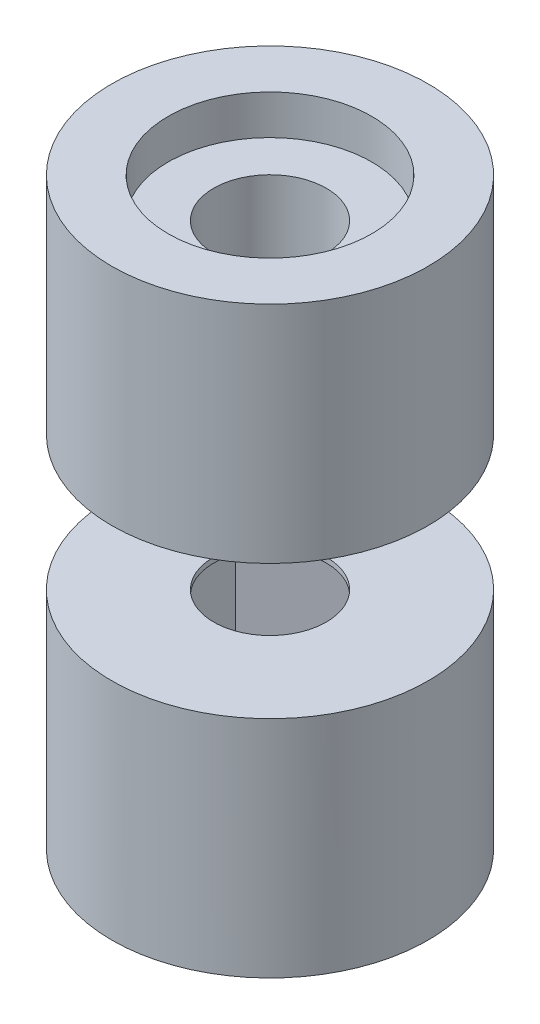
SolidWorks part; units mm, degrees
ref_plane "Front Plane" through (0, 0, 0) normal (0, 0, 1) x (1, 0, 0)
ref_plane "Top Plane" through (0, 0, 0) normal (0, 1, 0) x (1, 0, 0)
ref_plane "Right Plane" through (0, 0, 0) normal (1, 0, 0) x (0, 0, -1)
sketch "Sketch1" plane through (0, 0, 0) normal (0, 1, 0) x (1, 0, 0)
  circle A0 centre (0, 0) radius 8
extrude "Boss-Extrude1" add sketch "Sketch1" along normal blind 29.524
sketch "Sketch2" plane through (0, 0, 0) normal (0, 0, 1) x (1, 0, 0)
  line L0 (-10.2, 11.362) -> (10.2, 11.362)
  line L1 (10.2, 11.362) -> (10.2, 18.162)
  line L2 (10.2, 18.162) -> (-10.2, 18.162)
  line L3 (-10.2, 18.162) -> (-10.2, 11.362)
extrude "Cut-Extrude1" cut sketch "Sketch2" against normal through all and the other way through all
sketch "Sketch3" plane through (0, 0, 0) normal (0, 1, 0) x (1, 0, 0)
  circle A0 centre (0, 0) radius 2.85
extrude "Cut-Extrude2" cut sketch "Sketch3" along normal blind 29.524
ref_plane "Plane1" through (0, 29.524, 0) normal (0, 1, 0) x (1, 0, 0)
sketch "Sketch4" plane through (0, 29.524, 0) normal (0, 1, 0) x (1, 0, 0)
  circle A0 centre (0, 0) radius 5.15
extrude "Cut-Extrude3" cut sketch "Sketch4" against normal blind 2
sketch "Sketch5" plane through (0, 0, 0) normal (0, 1, 0) x (1, 0, 0)
  line L0 (4.1, -2.3671) -> (0, -4.7343)
  line L1 (0, -4.7343) -> (-4.1, -2.3671)
  line L2 (-4.1, -2.3671) -> (-4.1, 2.3671)
  line L3 (-4.1, 2.3671) -> (0, 4.7343)
  line L4 (0, 4.7343) -> (4.1, 2.3671)
  line L5 (4.1, 2.3671) -> (4.1, -2.3671)
extrude "Cut-Extrude4" cut sketch "Sketch5" along normal blind 11.1
